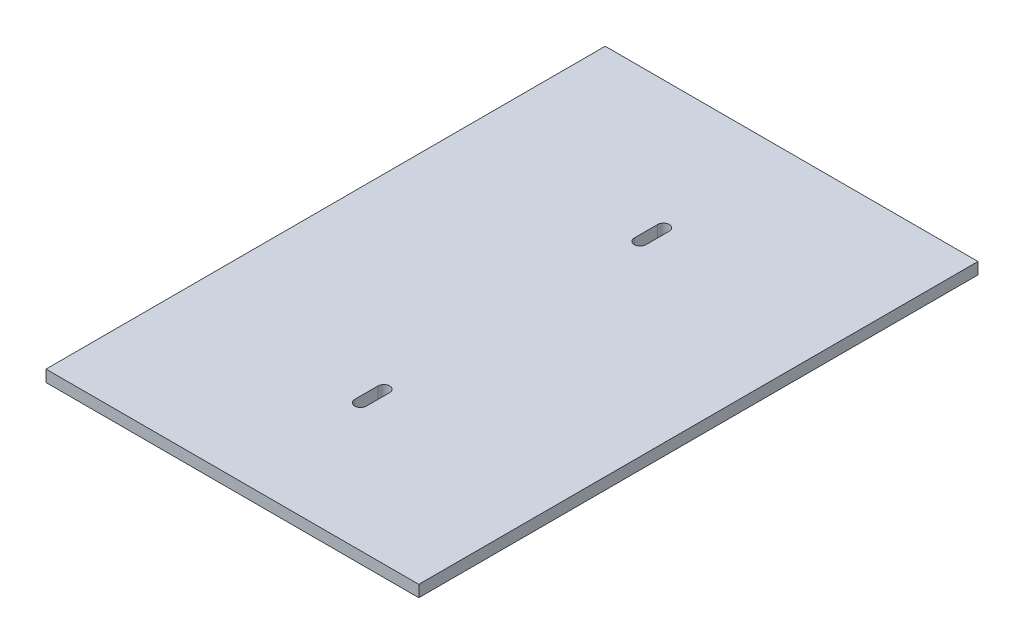
SolidWorks part; units mm, degrees
material "ASTM A36 Steel"
ref_plane "Front Plane" through (0, 0, 0) normal (0, 0, 1) x (1, 0, 0)
ref_plane "Top Plane" through (0, 0, 0) normal (0, 1, 0) x (1, 0, 0)
ref_plane "Right Plane" through (0, 0, 0) normal (1, 0, 0) x (0, 0, -1)
sketch "Sketch1" plane through (0, 0, 0) normal (0, 1, 0) x (1, 0, 0)
  line L0 (0, -69.85) -> (0, -82.55) construction
  line L1 (-101.6, -152.4) -> (101.6, -152.4)
  line L2 (-101.6, -152.4) -> (-101.6, 152.4)
  line L3 (-101.6, 152.4) -> (101.6, 152.4)
  line L4 (101.6, -152.4) -> (101.6, 152.4)
  line L5 (-101.6, -152.4) -> (101.6, 152.4) construction
  line L6 (-101.6, 152.4) -> (101.6, -152.4) construction
  line L7 (-101.6, 0) -> (101.6, 0) construction
  line L8 (3.175, -69.85) -> (3.175, -82.55)
  line L9 (-3.175, -69.85) -> (-3.175, -82.55)
  line L10 (0, 69.85) -> (0, 82.55) construction
  line L11 (3.175, 69.85) -> (3.175, 82.55)
  line L12 (-3.175, 69.85) -> (-3.175, 82.55)
  arc A0 (3.175, -69.85) -> (-3.175, -69.85) centre (0, -69.85) ccw
  arc A1 (-3.175, -82.55) -> (3.175, -82.55) centre (0, -82.55) ccw
  arc A2 (3.175, 69.85) -> (-3.175, 69.85) centre (0, 69.85) cw
  arc A3 (-3.175, 82.55) -> (3.175, 82.55) centre (0, 82.55) cw
  point P0 (0, 0)
  point P8 (0, -76.2)
  point P16 (0, 76.2)
  dimension "D3" = 12.7
  dimension "D4" = 3.175
  dimension "D5" = 76.2
  dimension "D1" = 203.2
  dimension "D2" = 304.8
extrude "Boss-Extrude1" add sketch "Sketch1" along normal blind 6.35
